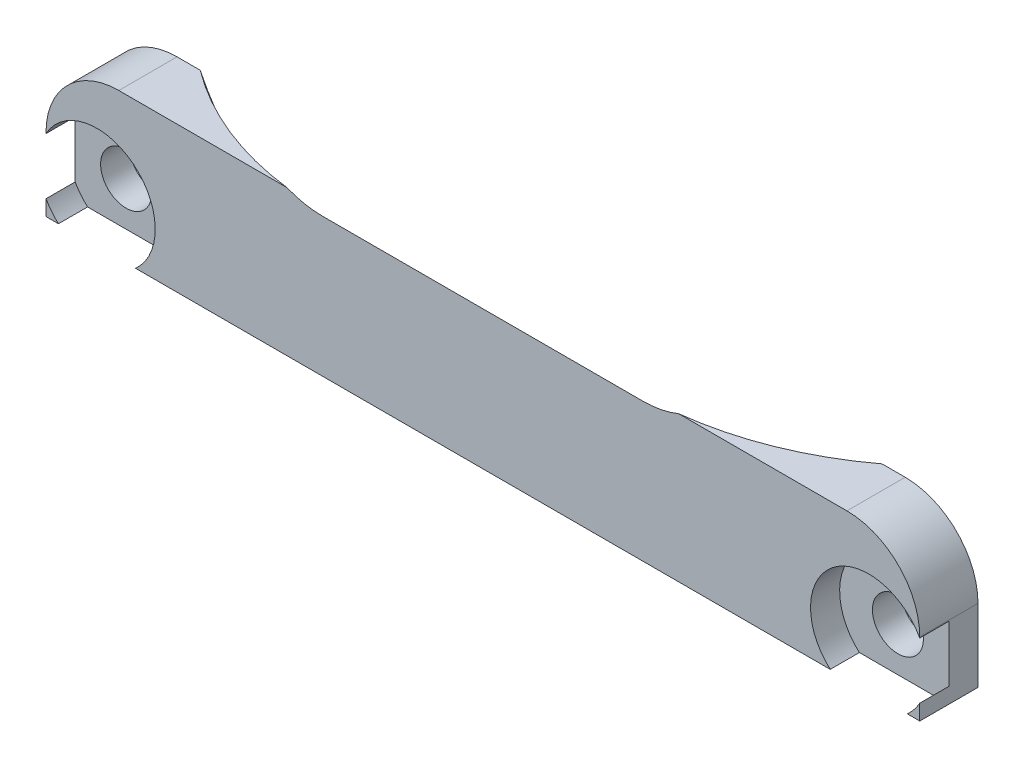
SolidWorks part; units mm, degrees
ref_plane "Front Plane" through (0, 0, 0) normal (0, 0, 1) x (1, 0, 0)
ref_plane "Top Plane" through (0, 0, 0) normal (0, 1, 0) x (1, 0, 0)
ref_plane "Right Plane" through (0, 0, 0) normal (1, 0, 0) x (0, 0, -1)
sketch "Sketch1" plane through (0, 0, 0) normal (0, 0, 1) x (1, 0, 0)
  line L1 (-30, 5) -> (30, 5)
  line L2 (-30, 5) -> (-30, -5)
  line L3 (-30, -5) -> (30, -5)
  line L4 (30, 5) -> (30, -5)
  line L5 (-30, 5) -> (30, -5) construction
  line L6 (-30, -5) -> (30, 5) construction
  point P0 (0, 0)
  dimension "D1" = 60
  dimension "D2" = 10
extrude "Boss-Extrude1" add sketch "Sketch1" along normal mid plane 41
sketch "Sketch2" plane through (0, 0, 0) normal (0, 0, 1) x (1, 0, 0)
  line L0 (-32.5, 11) -> (32.5, 11)
  line L1 (0, 11) -> (0, 0) construction
  line L2 (-11, -10.5) -> (11, -10.5)
  line L3 (30, 5) -> (-30, 5) construction
  arc A0 (-32.5, 11) -> (-11, -10.5) centre (-11, 11) ccw
  arc A1 (32.5, 11) -> (11, -10.5) centre (11, 11) cw
  point P9 (0, 0)
  dimension "D2" = 21.5
  dimension "D1" = 65
  dimension "D3" = 6
revolve "Cut-Revolve1" cut sketch "Sketch2" angle 360 about L0
sketch "Sketch3" plane through (0, 5, 0) normal (0, 1, 0) x (1, 0, 0)
  line L0 (30, -20.5) -> (30, -8.0777) construction
  line L1 (-30, 20.5) -> (30, 20.5)
  line L2 (-30, 20.5) -> (-30, -16.5)
  line L3 (-30, -16.5) -> (30, -16.5)
  line L4 (30, 20.5) -> (30, -16.5)
  line L5 (30, -20.5) -> (13.4495, -20.5) construction
  dimension "D1" = 4
extrude "Cut-Extrude1" cut sketch "Sketch3" against normal through all
fillet "Fillet1" radius 5 2 edges at (30, 5, 18.5) (-30, 5, 18.5)
sketch "Sketch4" plane through (0, 0, 20.5) normal (0, 0, 1) x (1, 0, 0)
  line L0 (-26.5, -2) -> (26.5, -2) construction
  line L1 (0, -2) -> (0, 0) construction
  line L2 (-30, -5) -> (30, -5) construction
  circle A0 centre (-26.5, -2) radius 1.75
  circle A1 centre (26.5, -2) radius 1.75
  dimension "D1" = 3.5
  dimension "D2" = 53
  dimension "D3" = 3
extrude "Cut-Extrude2" cut sketch "Sketch4" against normal through all
sketch "Sketch5" plane through (0, 0, 20.5) normal (0, 0, 1) x (1, 0, 0)
  circle A1 centre (-26.5, -2) radius 4
  circle A2 centre (26.5, -2) radius 4
  dimension "D1" = 8
extrude "Cut-Extrude5" cut sketch "Sketch5" against normal blind 2
